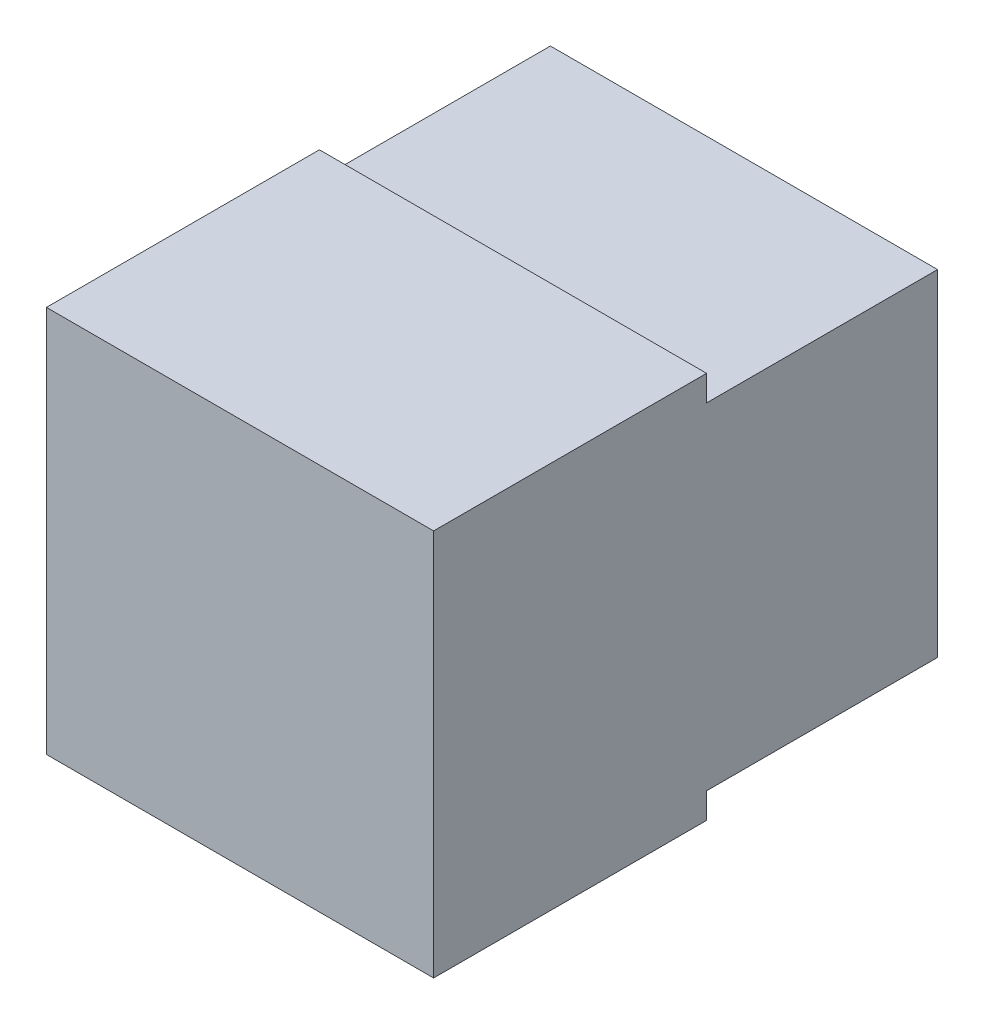
SolidWorks part; units mm, degrees
ref_plane "Front Plane" through (0, 0, 0) normal (0, 0, 1) x (1, 0, 0)
ref_plane "Top Plane" through (0, 0, 0) normal (0, 1, 0) x (1, 0, 0)
ref_plane "Right Plane" through (0, 0, 0) normal (1, 0, 0) x (0, 0, -1)
sketch "Sketch1" plane through (0, 0, 0) normal (0, 0, 1) x (-1, 0, 0)
  line L1 (-23.0489, -23.0489) -> (23.0489, -23.0489)
  line L2 (-23.0489, -23.0489) -> (-23.0489, 23.0489)
  line L3 (-23.0489, 23.0489) -> (23.0489, 23.0489)
  line L4 (23.0489, -23.0489) -> (23.0489, 23.0489)
  line L5 (-23.0489, -23.0489) -> (23.0489, 23.0489) construction
  line L6 (-23.0489, 23.0489) -> (23.0489, -23.0489) construction
  point P0 (0, 0)
extrude "Boss-Extrude1" add sketch "Sketch1" against normal blind 32.5
sketch "Sketch2" plane through (0, 0, -32.5) normal (0, 0, -1) x (-1, 0, 0)
  line L0 (-23.0489, -23.0489) -> (-23.0489, 23.0489) construction
  line L1 (23.0489, 19.9989) -> (-23.0489, 19.9989)
  line L2 (23.0489, 19.9989) -> (23.0489, -19.9989)
  line L3 (23.0489, -19.9989) -> (-23.0489, -19.9989)
  line L4 (-23.0489, 19.9989) -> (-23.0489, -19.9989)
  line L5 (23.0489, 19.9989) -> (-23.0489, -19.9989) construction
  line L6 (23.0489, -19.9989) -> (-23.0489, 19.9989) construction
  line L7 (23.0489, -23.0489) -> (-23.0489, -23.0489) construction
  point P0 (0, 0)
  dimension "D1" = 3.05
extrude "Boss-Extrude2" add sketch "Sketch2" along normal blind 27.5
equation "\"D1@Boss-Extrude1\"=60-27.5"
